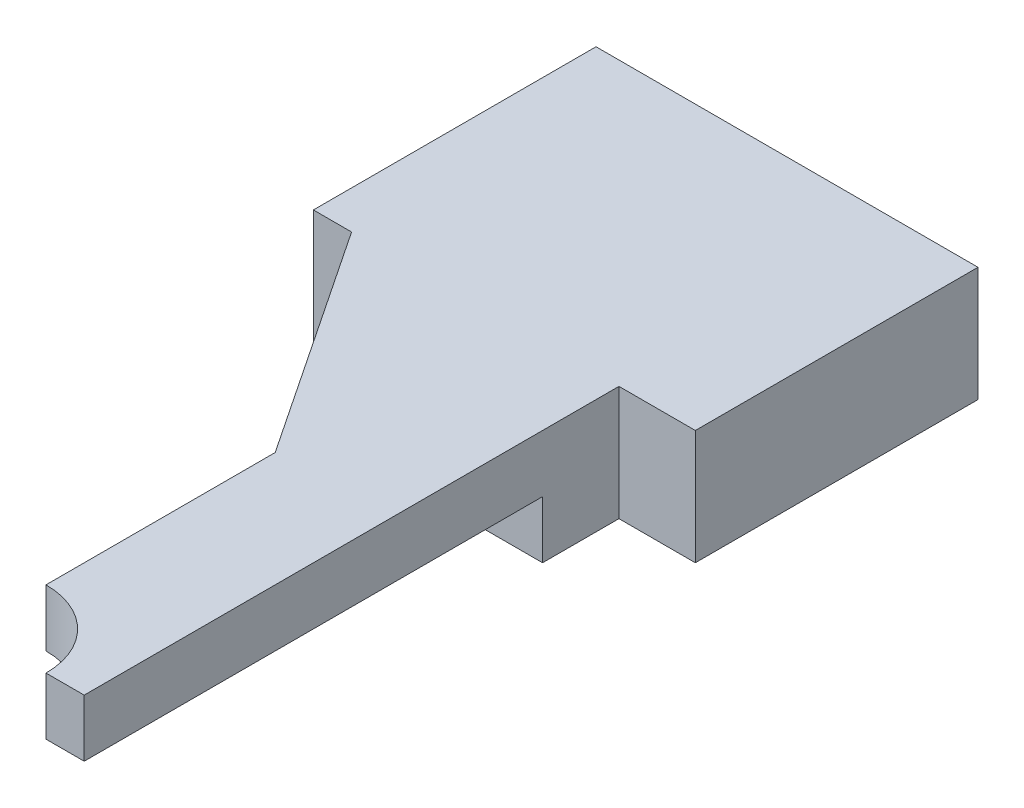
SolidWorks part; units mm, degrees
ref_plane "정면" through (0, 0, 0) normal (0, 0, 1) x (1, 0, 0)
ref_plane "윗면" through (0, 0, 0) normal (0, 1, 0) x (1, 0, 0)
ref_plane "우측면" through (0, 0, 0) normal (1, 0, 0) x (0, 0, -1)
sketch "스케치1" plane through (0, 0, 0) normal (0, 0, 1) x (1, 0, 0)
  line L1 (-25, 7.5) -> (25, 7.5)
  line L2 (-25, 7.5) -> (-25, -7.5)
  line L3 (-25, -7.5) -> (25, -7.5)
  line L4 (25, 7.5) -> (25, -7.5)
  line L5 (-25, 7.5) -> (25, -7.5) construction
  line L6 (-25, -7.5) -> (25, 7.5) construction
  point P0 (0, 0)
  dimension "D1" = 50
  dimension "D2" = 15
extrude "보스-돌출1" add sketch "스케치1" along normal blind 60
sketch "스케치2" plane through (0, 0, 60) normal (0, 0, 1) x (1, 0, 0)
  line L0 (25, 7.5) -> (-25, 7.5) construction
  line L1 (15, 7.5) -> (0, 7.5)
  line L2 (15, 7.5) -> (15, -7.5)
  line L3 (15, -7.5) -> (0, -7.5)
  line L4 (0, 7.5) -> (0, -7.5)
  line L5 (-25, -7.5) -> (25, -7.5) construction
  dimension "D1" = 15
extrude "보스-돌출2" add sketch "스케치2" along normal blind 60
sketch "스케치3" plane through (0, 0, 120) normal (0, 0, 1) x (1, 0, 0)
  line L0 (0, 7.5) -> (0, -7.5) construction
  line L1 (15, -7.5) -> (0, -7.5)
  line L2 (15, -7.5) -> (15, 0)
  line L3 (15, 0) -> (0, 0)
  line L4 (0, -7.5) -> (0, 0)
extrude "컷-돌출1" cut sketch "스케치3" against normal blind 60
sketch "스케치4" plane through (0, 7.5, 0) normal (0, 1, 0) x (1, 0, 0)
  line L0 (0, -120) -> (0, -60) construction
  line L1 (15, -120) -> (0, -120) construction
  line L2 (0, -110) -> (0, -120)
  line L3 (0, -120) -> (10, -120)
  arc A0 (0, -110) -> (10, -120) centre (0, -120) cw
  dimension "D1" = 10
extrude "컷-돌출2" cut sketch "스케치4" against normal blind 10
sketch "스케치6" plane through (0, 7.5, 0) normal (0, 1, 0) x (1, 0, 0)
  line L1 (25, -60) -> (15, -60)
  line L2 (25, -60) -> (25, -50)
  line L3 (25, -50) -> (15, -50)
  line L4 (15, -60) -> (15, -50)
  line L5 (-25, -60) -> (0, -60)
  line L6 (-25, -60) -> (-25, -50)
  line L7 (-25, -50) -> (0, -50)
  line L8 (0, -60) -> (0, -50)
  dimension "D1" = 10
  dimension "D2" = 10
  dimension "D3" = 10
  dimension "D4" = 25
extrude "컷-돌출3" cut sketch "스케치6" against normal blind 20
sketch "스케치5" plane through (0, 7.5, 0) normal (0, 1, 0) x (1, 0, 0)
  line L0 (0, -50) -> (0, -80)
  line L1 (0, -110) -> (0, -50) construction
  line L2 (0, -80) -> (-20, -50)
  line L4 (-20, -50) -> (0, -50)
  line L6 (0, -50) -> (-25, -50) construction
  dimension "D1" = 20
  dimension "D2" = 30
  dimension "D3" = 0
extrude "보스-돌출3" add sketch "스케치5" against normal blind 7.5
sketch "스케치7" plane through (0, -7.5, 0) normal (0, -1, 0) x (1, 0, 0)
  line L0 (-25, 0) -> (25, 0) construction
  line L1 (-41.0789, -13) -> (41.0789, -13)
  line L2 (-41.0789, -13) -> (-41.0789, 13)
  line L3 (-41.0789, 13) -> (41.0789, 13)
  line L4 (41.0789, -13) -> (41.0789, 13)
  line L5 (-41.0789, -13) -> (41.0789, 13) construction
  line L6 (-41.0789, 13) -> (41.0789, -13) construction
  point P0 (0, 0)
  dimension "D1" = 13
extrude "컷-돌출4" cut sketch "스케치7" against normal through all both and the other way through all
